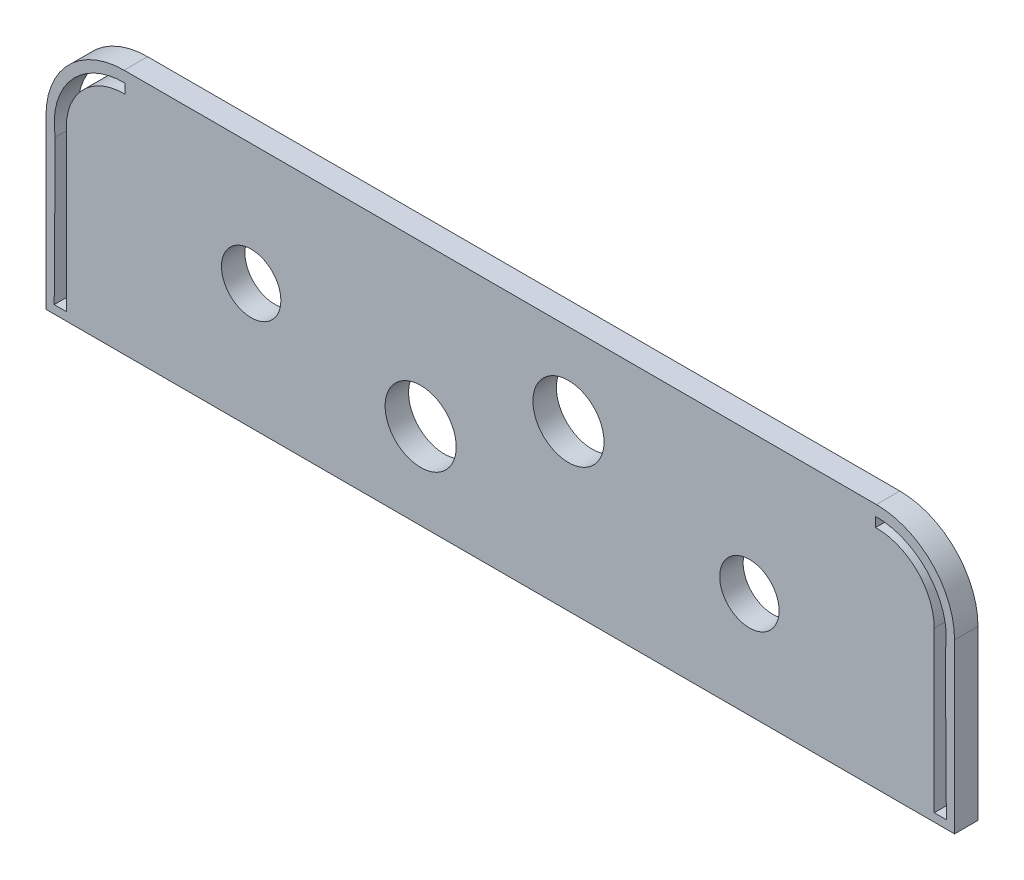
SolidWorks part; units mm, degrees
ref_plane "Front Plane" through (0, 0, 0) normal (0, 0, 1) x (1, 0, 0)
ref_plane "Top Plane" through (0, 0, 0) normal (0, 1, 0) x (1, 0, 0)
ref_plane "Right Plane" through (0, 0, 0) normal (1, 0, 0) x (0, 0, -1)
sketch "Sketch1" plane through (0, 0, 0) normal (0, 0, 1) x (1, 0, 0)
  line L0 (58.125, -2.25) -> (-58.125, -2.25) construction
  line L1 (-48.125, 15.75) -> (48.125, 15.75)
  line L2 (-58.125, 5.75) -> (-58.125, -15.75)
  line L3 (-58.125, -15.75) -> (58.125, -15.75)
  line L4 (58.125, 5.75) -> (58.125, -15.75)
  line L5 (-58.125, 15.75) -> (58.125, -15.75) construction
  line L6 (-58.125, -15.75) -> (58.125, 15.75) construction
  line L7 (31.875, 15.75) -> (31.875, -15.75) construction
  line L8 (-31.875, -15.75) -> (-31.875, 15.75) construction
  line L9 (-58.125, -0.25) -> (58.125, -0.25) construction
  arc A0 (48.125, 15.75) -> (58.125, 5.75) centre (48.125, 5.75) cw
  arc A1 (-48.125, 15.75) -> (-58.125, 5.75) centre (-48.125, 5.75) ccw
  circle A2 centre (31.875, -2.25) radius 3.8
  circle A3 centre (-31.875, 0.25) radius 3.8
  point P0 (0, 0)
  dimension "D3" = 10
  dimension "D6" = 7.6
  dimension "D8" = 7.6
  dimension "D1" = 116.25
  dimension "D2" = 31.5
  dimension "D4" = 13.5
  dimension "D5" = 26.25
  dimension "D7" = 15.5
  dimension "D9" = 26.25
extrude "Boss-Extrude2" add sketch "Sketch1" along normal blind 3
sketch "Sketch2" plane through (0, 0, 3) normal (0, 0, 1) x (1, 0, 0)
  line L0 (-18.625, 15.75) -> (-18.625, -15.75) construction
  line L1 (48.125, 15.75) -> (-48.125, 15.75) construction
  line L2 (-58.125, -15.75) -> (58.125, -15.75) construction
  line L3 (21.625, 15.75) -> (21.625, -15.75) construction
  line L4 (-58.125, 5.25) -> (58.125, 5.25) construction
  line L5 (-58.125, 5.75) -> (-58.125, -15.75) construction
  line L6 (58.125, -15.75) -> (58.125, 5.75) construction
  line L7 (8.725, 15.75) -> (8.725, -15.75) construction
  line L8 (-10.185, 15.75) -> (-10.185, -15.75) construction
  line L9 (-58.125, -4.75) -> (58.125, -4.75) construction
  line L10 (0.575, 5.25) -> (0.575, -15.75) construction
  line L11 (-18.335, -4.75) -> (-18.335, -15.75) construction
  line L26 (55.625, -15.75) -> (55.625, 5.75)
  line L27 (55.625, -15.75) -> (55.625, 5.75)
  line L28 (-55.625, -15.75) -> (-58.125, -15.75)
  line L29 (-55.625, 5.75) -> (-55.625, -15.75)
  line L30 (-55.625, 5.75) -> (-55.625, -15.75)
  line L31 (-58.125, -15.75) -> (-58.125, 5.25)
  line L32 (-48.125, 13.25) -> (-48.125, 15.75)
  line L33 (55.625, -15.75) -> (58.125, -15.75)
  line L34 (58.125, -15.75) -> (58.125, 5.25)
  line L35 (48.125, 13.25) -> (48.125, 15.75)
  circle A0 centre (-31.875, 0.25) radius 13.25 construction
  circle A1 centre (31.875, -2.25) radius 10.25 construction
  circle A2 centre (8.725, 5.25) radius 18 construction
  circle A3 centre (8.725, 5.25) radius 4.4
  circle A4 centre (8.725, 5.25) radius 8.15 construction
  circle A5 centre (-10.185, -4.75) radius 8.15 construction
  circle A6 centre (-10.185, -4.75) radius 4.4
  arc A10 (58.125, 5.75) -> (48.125, 15.75) centre (48.125, 5.75) ccw
  arc A11 (58.125, 5.75) -> (48.125, 15.75) centre (48.125, 5.75) ccw
  arc A13 (-48.125, 15.75) -> (-58.125, 5.75) centre (-48.125, 5.75) ccw
  arc A14 (-48.125, 15.75) -> (-58.125, 5.75) centre (-48.125, 5.75) ccw
  arc A28 (55.625, 5.75) -> (48.125, 13.25) centre (48.125, 5.75) ccw
  arc A29 (55.625, 5.75) -> (48.125, 13.25) centre (48.125, 5.75) ccw
  arc A32 (-48.125, 13.25) -> (-55.625, 5.75) centre (-48.125, 5.75) ccw
  arc A33 (-48.125, 13.25) -> (-55.625, 5.75) centre (-48.125, 5.75) ccw
  line M2 (58.125, -15.75) -> (58.125, 5.75)
  arc M3 (58.125, 5.75) -> (48.125, 15.75) centre (48.125, 5.75) ccw
  arc M5 (-48.125, 15.75) -> (-58.125, 5.75) centre (-48.125, 5.75) ccw
  line M6 (-58.125, 5.75) -> (-58.125, -15.75)
  line M7 (-58.125, -15.75) -> (58.125, -15.75)
  dimension "D1" = 26.5
  dimension "D2" = 20.5
  dimension "D6" = 8.8
  dimension "D8" = 10.76
  dimension "D9" = 8.8
  dimension "D10" = 19.2
  dimension "D7" = 31.5
  dimension "D11" = 11
  dimension "16" = 16.3
  dimension "D12" = 16.3
  dimension "D13" = 36
  dimension "D14" = 8.44
  dimension "D16" = 2.5
  dimension "D3" = 40.25
  dimension "D4" = 12.9
  dimension "D15" = 0.29
  dimension "D20" = 21
  dimension "D17" = 2.5
  dimension "D18" = 0
  dimension "D19" = 0
other "AlignGroup1"
other "AlignGroup2"
other "AlignGroup3"
other "AlignGroup4"
other "AlignGroup5"
extrude "Boss-Extrude3" add sketch "Sketch2" along normal blind 25 contours A3 | A6 | A29 L27 L35 M7 M2 M3 | A33 L32 L30 M5 M6 M7
sketch "Sketch5" plane through (0, 0, 28) normal (0, 0, 1) x (1, 0, 0)
  line L0 (55.525, -14.7) -> (55.525, 5.75)
  line L1 (48.025, 13.1493) -> (48.025, 14.3846)
  line L2 (56.9469, 3.9266) -> (57.0757, -14.7)
  line L3 (55.525, -14.7) -> (57.0757, -14.7)
  line L5 (0, 15.75) -> (0, -15.75) construction
  line L6 (48.125, 15.75) -> (-48.125, 15.75) construction
  line L7 (-55.625, -15.75) -> (55.625, -15.75) construction
  line L20 (-56.9469, 3.9266) -> (-57.0757, -14.7)
  line L22 (-55.525, -14.7) -> (-57.0757, -14.7)
  line L36 (-55.525, -14.7) -> (-55.525, 5.75)
  line L37 (-48.025, 13.1493) -> (-48.025, 14.3846)
  arc A0 (48.025, 13.1493) -> (55.525, 5.75) centre (48.125, 5.75) cw
  arc A1 (48.025, 14.3846) -> (56.9469, 3.9266) centre (48.125, 5.4352) cw
  arc A8 (-48.025, 14.3846) -> (-56.9469, 3.9266) centre (-48.125, 5.4352) ccw
  arc A9 (-48.025, 13.1493) -> (-55.525, 5.75) centre (-48.125, 5.75) ccw
sketch "Sketch10" plane through (0, 0, 28) normal (0, 0, 1) x (1, 0, 0)
  circle A1 centre (8.725, 5.25) radius 4.4
  circle A2 centre (8.725, 5.25) radius 4.4
  circle A3 centre (-10.185, -4.75) radius 4.4
  circle A4 centre (-10.185, -4.75) radius 4.4
  dimension "D1" = 0
  dimension "D2" = 0
extrude "Cut-Extrude3" cut sketch "Sketch10" against normal blind 1
extrude "Cut-Extrude4" cut sketch "Sketch5" against normal blind 50
sketch "Sketch12" plane through (0, 0, 27) normal (0, 0, 1) x (1, 0, 0)
  circle A3 centre (-10.185, -4.75) radius 4.55
  circle A5 centre (-10.185, -4.75) radius 4.55
  circle A7 centre (8.725, 5.25) radius 4.55
  circle A8 centre (8.725, 5.25) radius 4.55
  dimension "D1" = 0.15
  dimension "D2" = 0.15
extrude "Cut-Extrude6" cut sketch "Sketch12" against normal blind 50
sketch "Sketch13" plane through (0, 0, 28) normal (0, 0, 1) x (1, 0, 0)
  line L0 (57.0757, -14.7) -> (55.625, -14.7) construction
  line L1 (55.625, -14.7) -> (55.625, -15.75) construction
  line L2 (55.625, -15.75) -> (58.125, -15.75) construction
  line L3 (58.125, -15.75) -> (58.125, 5.75) construction
  line L4 (48.125, 15.75) -> (48.125, 14.3852) construction
  line L5 (56.9469, 3.9266) -> (57.0757, -14.7) construction
  line L6 (-48.125, 14.3852) -> (-48.125, 15.75) construction
  line L7 (-58.125, 5.75) -> (-58.125, -15.75) construction
  line L8 (-58.125, -15.75) -> (-55.625, -15.75) construction
  line L9 (-55.625, -15.75) -> (-55.625, -14.7) construction
  line L10 (-55.625, -14.7) -> (-57.0757, -14.7) construction
  line L11 (-57.0757, -14.7) -> (-56.9469, 3.9266) construction
  line L12 (57.0757, -14.7) -> (55.625, -14.7)
  line L13 (55.625, -14.7) -> (55.625, -15.75)
  line L14 (55.625, -15.75) -> (58.125, -15.75)
  line L15 (58.125, -15.75) -> (58.125, 5.75)
  line L16 (48.125, 15.75) -> (48.125, 14.3852)
  line L17 (56.9469, 3.9266) -> (57.0757, -14.7)
  line L18 (-48.125, 14.3852) -> (-48.125, 15.75)
  line L19 (-58.125, 5.75) -> (-58.125, -15.75)
  line L20 (-58.125, -15.75) -> (-55.625, -15.75)
  line L21 (-55.625, -15.75) -> (-55.625, -14.7)
  line L22 (-55.625, -14.7) -> (-57.0757, -14.7)
  line L23 (-57.0757, -14.7) -> (-56.9469, 3.9266)
  arc A0 (58.125, 5.75) -> (48.125, 15.75) centre (48.125, 5.75) ccw construction
  arc A1 (56.9469, 3.9266) -> (48.125, 14.3852) centre (48.125, 5.4352) ccw construction
  arc A2 (-48.125, 14.3852) -> (-56.9469, 3.9266) centre (-48.125, 5.4352) ccw construction
  arc A3 (-48.125, 15.75) -> (-58.125, 5.75) centre (-48.125, 5.75) ccw construction
  arc A4 (58.125, 5.75) -> (48.125, 15.75) centre (48.125, 5.75) ccw
  arc A5 (56.9469, 3.9266) -> (48.125, 14.3852) centre (48.125, 5.4352) ccw
  arc A6 (-48.125, 14.3852) -> (-56.9469, 3.9266) centre (-48.125, 5.4352) ccw
  arc A7 (-48.125, 15.75) -> (-58.125, 5.75) centre (-48.125, 5.75) ccw
extrude "Cut-Extrude7" cut sketch "Sketch13" against normal up to surface (25 mm away) up to face at (-5.635, -4.75, 3)
